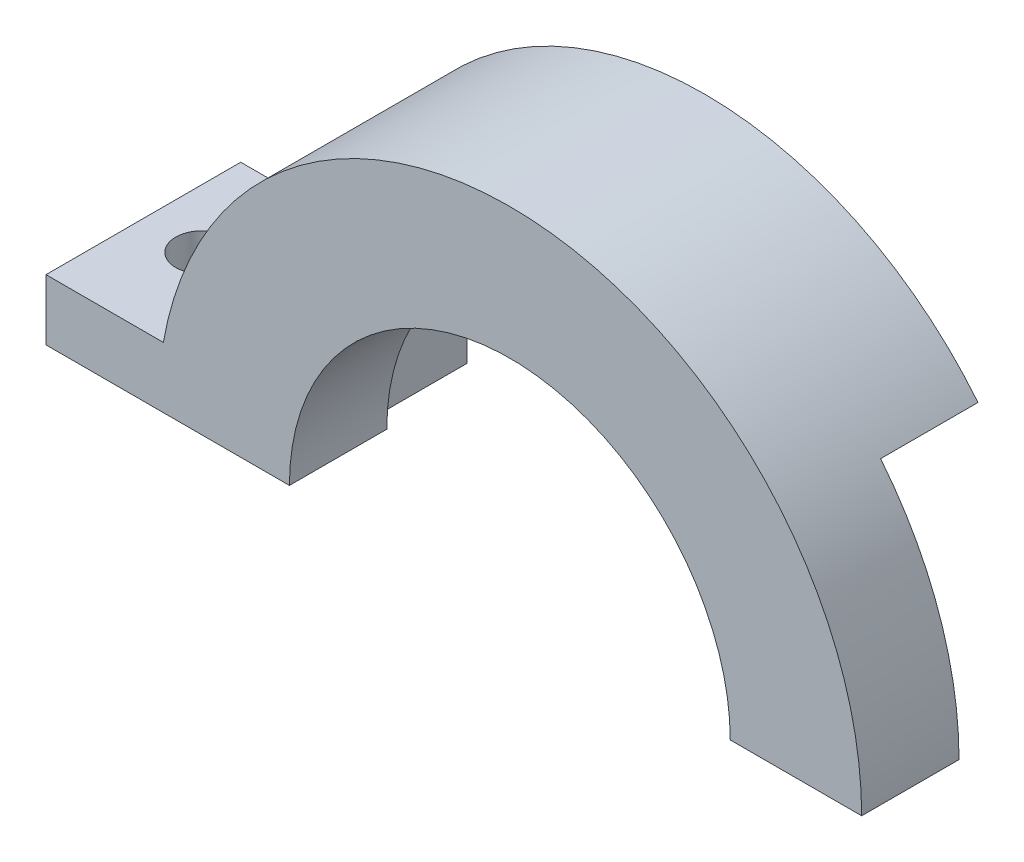
SolidWorks part; units mm, degrees
ref_plane "Front Plane" through (0, 0, 0) normal (0, 0, 1) x (1, 0, 0)
ref_plane "Top Plane" through (0, 0, 0) normal (0, 1, 0) x (1, 0, 0)
ref_plane "Right Plane" through (0, 0, 0) normal (1, 0, 0) x (0, 0, -1)
sketch "Sketch1" plane through (0, 0, 0) normal (0, 0, 1) x (1, 0, 0)
  line L1 (-19.5, 13.8306) -> (-19.5, 0)
  line L2 (-28.9068, 0) -> (-19.5, 0)
  line L3 (23.9068, 0) -> (28.9068, 0)
  arc A0 (23.9068, 0) -> (-19.5, 13.8306) centre (0, 0) ccw
  arc A1 (28.9068, 0) -> (-28.9068, 0) centre (0, 0) ccw
  dimension "D1" = 47.8136
  dimension "D2" = 5
  dimension "D3" = 19.5
extrude "Boss-Extrude1" add sketch "Sketch1" along normal blind 8
sketch "Sketch2" plane through (0, 0, 8) normal (0, 0, 1) x (1, 0, 0)
  line L0 (-28.9068, 0) -> (-18.1106, 0)
  line L1 (18.1106, 0) -> (28.9068, 0)
  arc A0 (18.1106, 0) -> (-18.1106, 0) centre (0, 0) ccw
  arc A1 (28.9068, 0) -> (-28.9068, 0) centre (0, 0) ccw
  dimension "D1" = 36.2211
extrude "Boss-Extrude2" add sketch "Sketch2" along normal blind 8
sketch "Sketch3" plane through (0, 0, 16) normal (0, 0, 1) x (1, 0, 0)
  line L1 (-28.9068, 0) -> (-38.1106, 0)
  line L3 (-28.4711, 5) -> (-38.1106, 5)
  line L4 (-38.1106, 0) -> (-38.1106, 5)
  arc A1 (-28.4711, 5) -> (-28.9068, 0) centre (0, 0) ccw
  dimension "D2" = 5
extrude "Boss-Extrude3" add sketch "Sketch3" against normal through all
sketch "Sketch4" plane through (0, 5, 0) normal (0, 1, 0) x (1, 0, 0)
  circle A1 centre (-33.2908, -8) radius 2.165
  point P5 (-33.2908, -8)
extrude "Cut-Extrude1" cut sketch "Sketch4" against normal through all
sketch "Sketch5" plane through (0, 0, 0) normal (0, 0, -1) x (-1, 0, 0)
  line L0 (0, 0) -> (-17.3471, 16.4503)
  line L1 (-43.0241, 25.1875) -> (-58.1332, -8.3123)
  line L2 (-58.1332, -8.3123) -> (0, 0)
  line L3 (38.1106, 0) -> (19.5, 0) construction
  line L5 (-17.3471, 16.4503) -> (-43.0241, 25.1875)
  arc A1 (19.5, 13.8306) -> (-23.9068, 0) centre (0, 0) ccw construction
  dimension "D1" = 136.52
extrude "Cut-Extrude2" cut sketch "Sketch5" against normal blind 8
